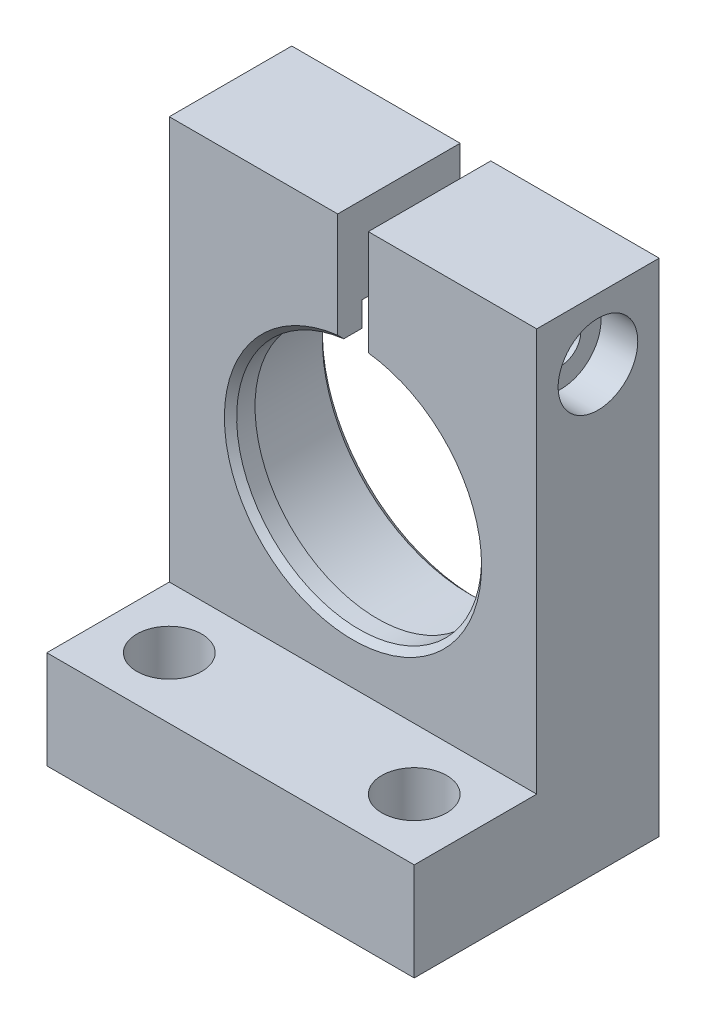
SolidWorks part; units mm, degrees
material "AISI 1045 Steel, cold drawn"
ref_plane "Front Plane" through (0, 0, 0) normal (0, 0, 1) x (1, 0, 0)
ref_plane "Top Plane" through (0, 0, 0) normal (0, 1, 0) x (1, 0, 0)
ref_plane "Right Plane" through (0, 0, 0) normal (1, 0, 0) x (0, 0, -1)
sketch "Sketch1" plane through (0, 0, 0) normal (0, 0, 1) x (1, 0, 0)
  line L1 (15, -21.9) -> (-15, -21.9)
  line L2 (15, -21.9) -> (15, 19)
  line L3 (15, 19) -> (-15, 19)
  line L4 (-15, -21.9) -> (-15, 19)
  line L5 (15, -21.9) -> (-15, 19) construction
  line L6 (15, 19) -> (-15, -21.9) construction
  circle A0 centre (0, 0) radius 12
  point P3 (0, -1.45)
  point P8 (0, 0)
  dimension "D1" = 24
  dimension "D2" = 19
  dimension "D3" = 21.9
  dimension "D4" = 30
extrude "Boss-Extrude1" add sketch "Sketch1" along normal blind 10
sketch "Sketch2" plane through (0, 0, 10) normal (0, 0, -1) x (-1, 0, 0)
  circle A0 centre (0, 0) radius 12 construction
  circle A1 centre (0, 0) radius 12
  circle A2 centre (0, 0) radius 10
  dimension "D1" = 20
extrude "Boss-Extrude2" add sketch "Sketch2" along normal blind 2
sketch "Sketch3" plane through (0, 0, 10) normal (0, 0, 1) x (1, 0, 0)
  line L0 (15, 19) -> (-15, 19) construction
  line L1 (1.25, 9.9216) -> (-1.25, 9.9216)
  line L2 (1.25, 9.9216) -> (1.25, 19)
  line L3 (1.25, 19) -> (-1.25, 19)
  line L4 (-1.25, 9.9216) -> (-1.25, 19)
  line L5 (1.25, 9.9216) -> (-1.25, 19) construction
  line L6 (1.25, 19) -> (-1.25, 9.9216) construction
  circle A0 centre (0, 0) radius 10 construction
  point P0 (0, 14.4608)
  point P7 (1.8148, 10.8493)
  point P10 (-1.9474, 10.8262)
  point P11 (0, 0)
  dimension "D1" = 2.5
extrude "Cut-Extrude1" cut sketch "Sketch3" against normal through all
hole_wizard "CBORE for M3 SHCS1" positions "Sketch4" profile "Sketch5" counterbore size "M3" standard "ANSI Metric"
sketch "Sketch4" plane through (15, 0, 0) normal (1, 0, 0) x (0, 0, -1)
  line L0 (0, -21.9) -> (0, 19) construction
  line L1 (-10, 19) -> (0, 19) construction
  point P0 (-5, 14)
  dimension "D1" = 5
  dimension "D2" = 5
sketch "Sketch5" plane through (15, 14, 5) normal (0, 1, 0) x (0, 0, -1)
  line L0 (0, 0) -> (0, 13.75)
  line L1 (0, 13.75) -> (1.6, 13.75)
  line L3 (1.6, 13.75) -> (1.6, 3)
  line L4 (1.6, 3) -> (3.25, 3)
  line L5 (3.25, 3) -> (3.25, 0)
  line L7 (3.25, 0) -> (0, 0)
  line L11 (0, -6.35) -> (0, 107.95) construction
  dimension "Thru Hole Dia." = 3.2
  dimension "Thru Hole Depth" = 13.75
  dimension "C'Bore Dia." = 6.5
  dimension "C'Bore Depth" = 3
hole_wizard "Tap Drill for M3x0.5 Tap1" positions "Sketch6" profile "Sketch7" hole size "M3x0.5" standard "ANSI Metric" end condition up to next
sketch "Sketch6" plane through (-15, 0, 0) normal (-1, 0, 0) x (0, 0, 1)
  line L0 (10, 19) -> (10, -21.9) construction
  line L1 (10, 19) -> (0, 19) construction
  point P0 (5, 14)
  dimension "D1" = 5
  dimension "D2" = 5
sketch "Sketch7" plane through (-15, 14, 5) normal (0, 1, 0) x (0, 0, 1)
  line L0 (0, 0) -> (0, 13.75)
  line L1 (0, 13.75) -> (1.25, 13.75)
  line L2 (1.25, 13.75) -> (1.25, 0)
  line L5 (1.25, 0) -> (0, 0)
  line L11 (0, -6.35) -> (0, 107.95) construction
  dimension "Thru Hole Dia." = 2.5
  dimension "Thru Hole Depth" = 13.75
chamfer "Chamfer1" distance 0.5 angle 45 2 edges at (0, -10, 10) (0, -12, 0)
sketch "Sketch8" plane through (0, -21.9, 0) normal (0, -1, 0) x (1, 0, 0)
  line L1 (-15, 10) -> (15, 10)
  line L2 (-15, 10) -> (-15, 20)
  line L3 (-15, 20) -> (15, 20)
  line L4 (15, 10) -> (15, 20)
  point P5 (15, 10)
  dimension "D1" = 10
extrude "Boss-Extrude3" add sketch "Sketch8" against normal blind 8
hole_wizard "M5 Clearance Hole1" positions "Sketch9" profile "Sketch10" hole size "M5" standard "ANSI Metric" end condition up to next
sketch "Sketch9" plane through (0, -13.9, 0) normal (0, 1, 0) x (1, 0, 0)
  line L0 (15, -20) -> (-15, -20) construction
  line L1 (-15, -20) -> (-15, -10) construction
  line L2 (0, -10) -> (0, -20) construction
  line L4 (-15, -10) -> (15, -10) construction
  point P0 (-10, -15)
  point P14 (10, -15)
  point P16 (0, 0)
  point P17 (0, -10)
  dimension "D1" = 5
  dimension "D2" = 5
sketch "Sketch10" plane through (-10, -13.9, 15) normal (1, 0, 0) x (0, 0, 1)
  line L0 (0, 0) -> (0, 8)
  line L1 (0, 8) -> (2.65, 8)
  line L2 (2.65, 8) -> (2.65, 0)
  line L5 (2.65, 0) -> (0, 0)
  line L11 (0, -6.35) -> (0, 107.95) construction
  dimension "Thru Hole Dia." = 5.3
  dimension "Thru Hole Depth" = 8
